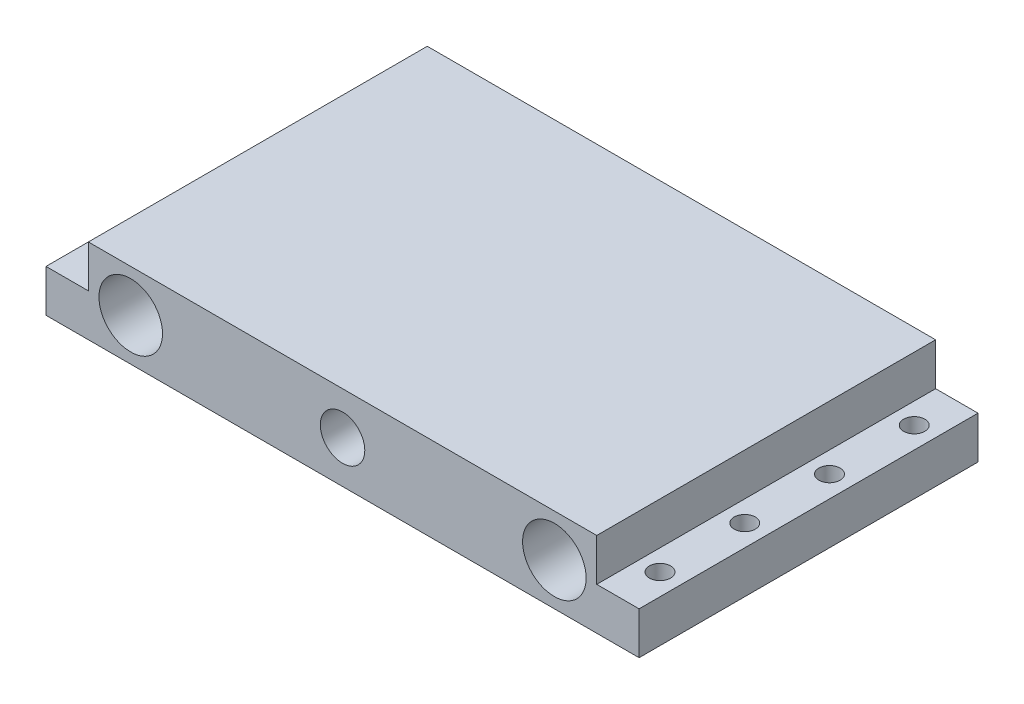
SolidWorks part; units mm, degrees
ref_plane "Front Plane" through (0, 0, 0) normal (0, 0, 1) x (1, 0, 0)
ref_plane "Top Plane" through (0, 0, 0) normal (0, 1, 0) x (1, 0, 0)
ref_plane "Right Plane" through (0, 0, 0) normal (1, 0, 0) x (0, 0, -1)
sketch "Sketch1" plane through (0, 0, 0) normal (0, 0, 1) x (1, 0, 0)
  line L1 (0, 0) -> (140, 0)
  line L2 (0, 0) -> (0, -20)
  line L3 (0, -20) -> (140, -20)
  line L4 (140, 0) -> (140, -20)
  dimension "D1" = 20
  dimension "D2" = 140
extrude "Boss-Extrude1" add sketch "Sketch1" along normal blind 80
sketch "Sketch2" plane through (0, 0, 0) normal (0, 1, 0) x (1, 0, 0)
  line L0 (140, -80) -> (0, -80) construction
  line L1 (140, 0) -> (130, 0)
  line L2 (140, 0) -> (140, -80)
  line L3 (140, -80) -> (130, -80)
  line L4 (130, 0) -> (130, -80)
  line L6 (0, 0) -> (10, 0)
  line L7 (0, 0) -> (0, -80)
  line L8 (0, -80) -> (10, -80)
  line L9 (10, 0) -> (10, -80)
  dimension "D1" = 10
  dimension "1" = 10
extrude "Cut-Extrude1" cut sketch "Sketch2" against normal blind 10
sketch "Sketch3" plane through (0, 0, 80) normal (0, 0, 1) x (1, 0, 0)
  line L2 (-53.7549, -10) -> (12.5, -10) construction
  line L3 (130, -10) -> (130, 0) construction
  circle A0 centre (20, -10) radius 7.5
  circle A1 centre (70, -10) radius 5.25
  circle A2 centre (120, -10) radius 7.5
  point P8 (45.5088, -10)
  point P16 (53.9236, -10)
  dimension "D2" = 15
  dimension "D3" = 10.5
  dimension "1.50" = 15
  dimension "D4" = 50
  dimension "D5" = 10
  dimension "5" = 50
extrude "Cut-Extrude2" cut sketch "Sketch3" against normal blind 80
sketch "Sketch4" plane through (0, -10, 0) normal (0, 1, 0) x (1, 0, 0)
  line L0 (10, 0) -> (0, 0) construction
  line L1 (70, 0) -> (70, -80) construction
  line L2 (130, 0) -> (10, 0) construction
  line L3 (130, -80) -> (10, -80) construction
  circle A0 centre (5.0563, -10) radius 2.5
  circle A1 centre (5.0563, -30) radius 2.5
  circle A2 centre (5.0563, -50) radius 2.5
  circle A3 centre (5.0563, -70) radius 2.5
  circle A4 centre (134.9437, -70) radius 2.5
  circle A5 centre (134.9437, -50) radius 2.5
  circle A6 centre (134.9437, -30) radius 2.5
  circle A7 centre (134.9437, -10) radius 2.5
  dimension "D1" = 5
  dimension "D2" = 20
  dimension "D3" = 10
  dimension "D4" = 20
  dimension "D5" = 20
extrude "Cut-Extrude4" cut sketch "Sketch4" against normal blind 440
